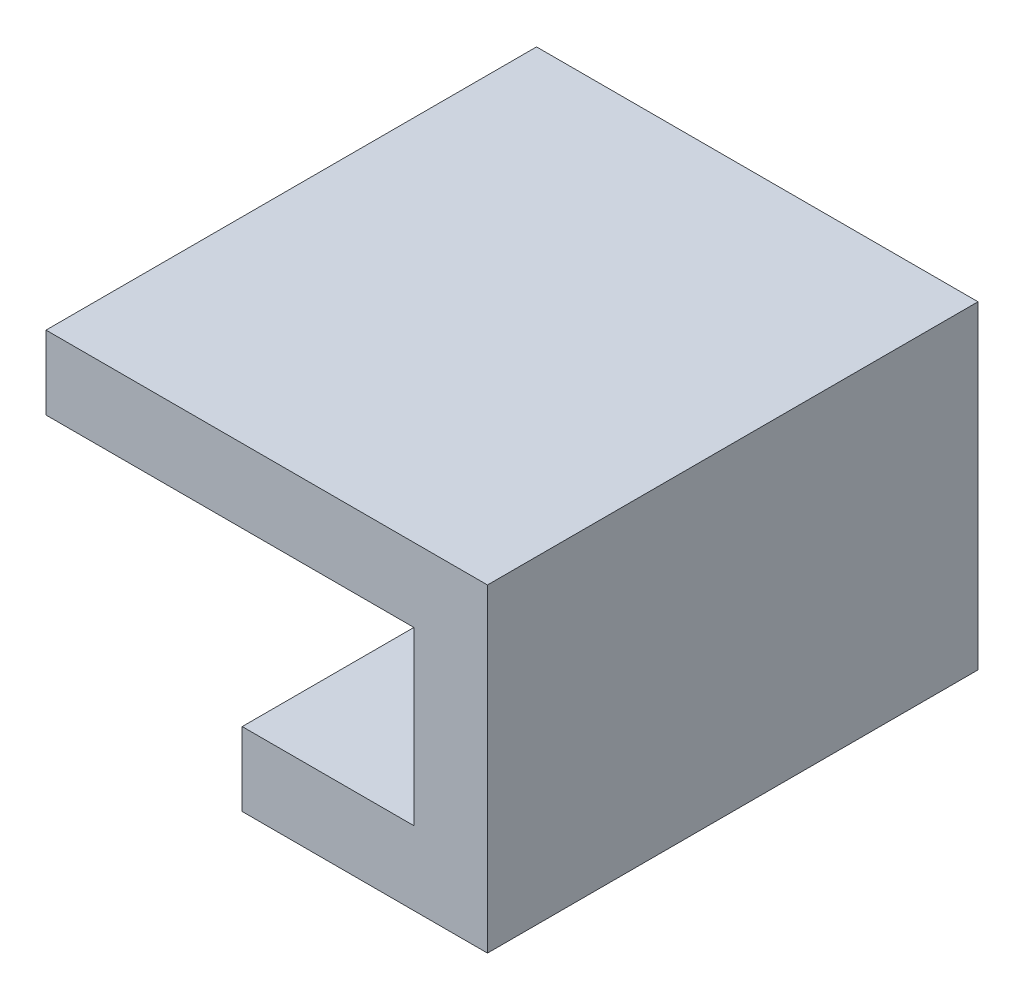
SolidWorks part; units mm, degrees
ref_plane "Front Plane" through (0, 0, 0) normal (0, 0, 1) x (1, 0, 0)
ref_plane "Top Plane" through (0, 0, 0) normal (0, 1, 0) x (1, 0, 0)
ref_plane "Right Plane" through (0, 0, 0) normal (1, 0, 0) x (0, 0, -1)
sketch "Sketch1" plane through (0, 0, 0) normal (0, 0, 1) x (1, 0, 0)
  line L0 (191.1871, -62.3117) -> (196.1871, -62.3117)
  line L1 (196.1871, -62.3117) -> (196.1871, -55.8117)
  line L2 (196.1871, -55.8117) -> (187.1871, -55.8117)
  line L3 (191.1871, -62.3117) -> (191.1871, -60.8117)
  line L4 (191.1871, -60.8117) -> (194.6871, -60.8117)
  line L5 (194.6871, -60.8117) -> (194.6871, -57.3117)
  line L6 (194.6871, -57.3117) -> (187.1871, -57.3117)
  line L7 (187.1871, -57.3117) -> (187.1871, -55.8117)
  dimension "D1" = 6.5
  dimension "D2" = 9
  dimension "D3" = 5
  dimension "D4" = 1.5
  dimension "D5" = 1.5
  dimension "D6" = 1.5
extrude "Boss-Extrude1" add sketch "Sketch1" along normal blind 10 contours L6 L7 L2 L1 L0 L3 L4 L5
